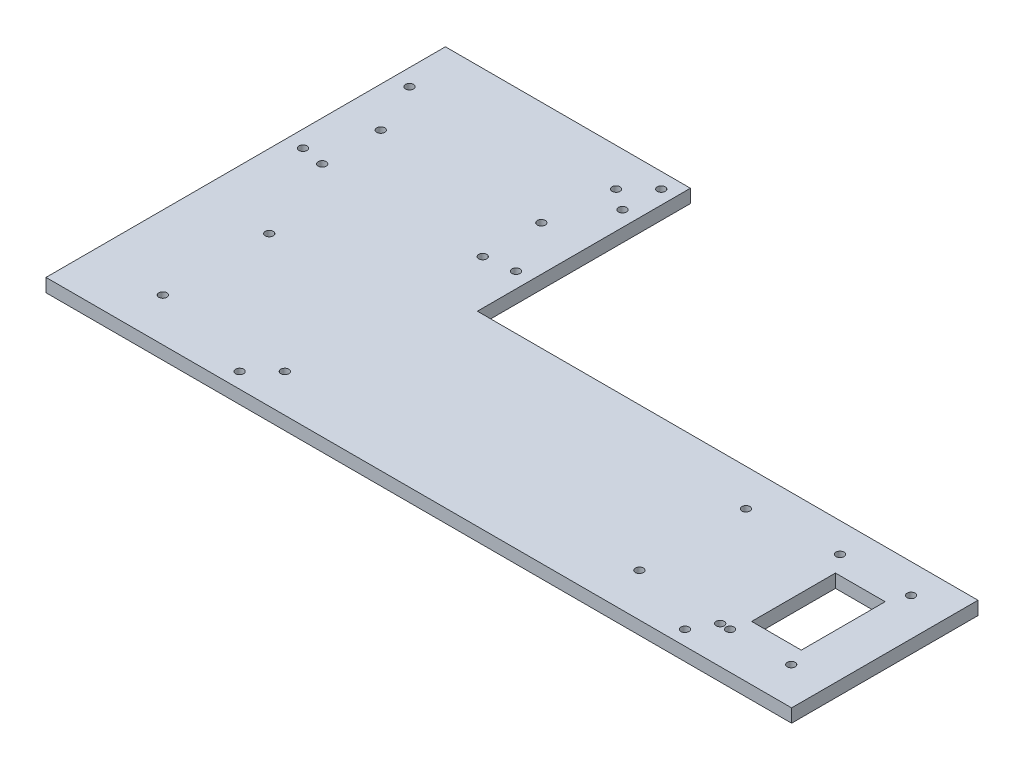
SolidWorks part; units mm, degrees
ref_plane "Front Plane" through (0, 0, 0) normal (0, 0, 1) x (1, 0, 0)
ref_plane "Top Plane" through (0, 0, 0) normal (0, 1, 0) x (1, 0, 0)
ref_plane "Right Plane" through (0, 0, 0) normal (1, 0, 0) x (0, 0, -1)
sketch "Sketch1" plane through (0, 0, 0) normal (0, 1, 0) x (1, 0, 0)
  line L1 (-124.5552, -60.7829) -> (155.4448, -60.7829)
  line L2 (-124.5552, -60.7829) -> (-124.5552, 9.2171)
  line L3 (-124.5552, 9.2171) -> (155.4448, 9.2171)
  line L4 (155.4448, -60.7829) -> (155.4448, 9.2171)
  line L6 (-124.5552, 9.2171) -> (-124.5552, 89.2171)
  line L7 (-124.5552, 89.2171) -> (-32.5552, 89.2171)
  line L8 (-32.5552, 9.2171) -> (-32.5552, 89.2171)
  line L9 (119.8304, -40.1838) -> (138.4894, -40.1838)
  line L10 (119.8304, -40.1838) -> (119.8304, -8.6968)
  line L11 (119.8304, -8.6968) -> (138.4894, -8.6968)
  line L12 (138.4894, -40.1838) -> (138.4894, -8.6968)
  circle A0 centre (141.3001, -46.7829) radius 1.5
  circle A1 centre (141.3001, -1.7829) radius 1.5
  circle A2 centre (114.6202, -1.7829) radius 1.5
  circle A3 centre (114.6202, -46.7829) radius 1.5
  circle A4 centre (82.1195, -44.6239) radius 1.5
  circle A5 centre (82.1195, -4.6239) radius 1.5
  circle A6 centre (-96.8805, -44.5794) radius 1.5
  circle A7 centre (-96.8805, -4.6239) radius 1.5
  circle A8 centre (-49.1247, -46.5403) radius 1.5
  circle A9 centre (-57.61, -55.0256) radius 1.5
  circle A10 centre (109.8601, -55.2612) radius 1.5
  circle A11 centre (118.3454, -46.7759) radius 1.5
  circle A12 centre (-37.7523, 83.4597) radius 1.5
  circle A13 centre (-46.2375, 74.9744) radius 1.5
  circle A14 centre (-118.3269, 69.4953) radius 1.5
  circle A15 centre (-118.3269, 29.4953) radius 1.5
  circle A16 centre (-38.3269, 29.4953) radius 1.5
  circle A17 centre (-38.3269, 69.4953) radius 1.5
  circle A18 centre (-109.6165, 49.9907) radius 1.5
  circle A19 centre (-109.6165, 27.9907) radius 1.5
  circle A20 centre (-49.3165, 49.9907) radius 1.5
  circle A21 centre (-49.3165, 27.9907) radius 1.5
  dimension "D5" = 3
  dimension "D6" = 3
  dimension "D7" = 3
  dimension "D8" = 3
  dimension "D9" = 3
  dimension "D10" = 3
  dimension "D11" = 3
  dimension "D12" = 3
  dimension "D13" = 3
  dimension "D14" = 3
  dimension "D1" = 280
  dimension "D2" = 70
  dimension "D3" = 92
  dimension "D4" = 150
extrude "Boss-Extrude1" add sketch "Sketch1" along normal blind 5 contours L1 L4 L3 L2 | L3 L8 L7 L6
